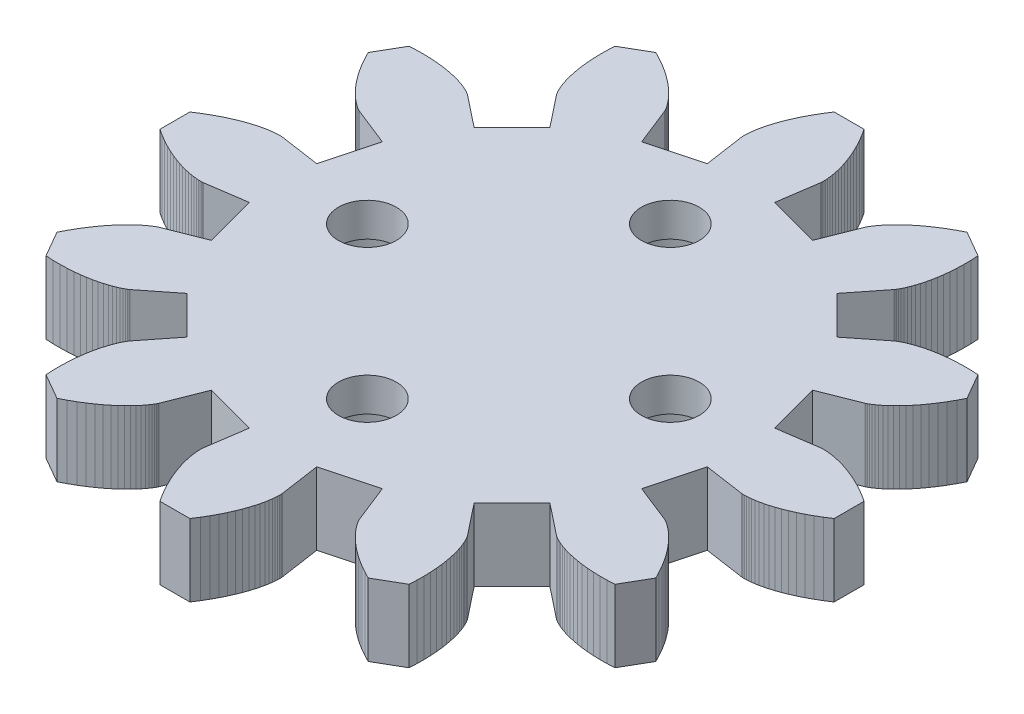
SolidWorks part; units mm, degrees
ref_plane "Front Plane" through (0, 0, 0) normal (0, 0, 1) x (1, 0, 0)
ref_plane "Top Plane" through (0, 0, 0) normal (0, 1, 0) x (1, 0, 0)
ref_plane "Right Plane" through (0, 0, 0) normal (1, 0, 0) x (0, 0, -1)
sketch "Sketch2" plane through (0, 0, 0) normal (0, 1, 0) x (1, 0, 0)
  line L0 (9.4981, 1.3948) -> (11.1567, 1.6383)
  line L1 (11.1567, 1.6383) -> (11.1651, 1.6393)
  line L2 (11.1651, 1.6393) -> (11.1903, 1.6415)
  line L3 (11.1903, 1.6415) -> (11.2326, 1.6435)
  line L4 (11.2326, 1.6435) -> (11.2917, 1.6441)
  line L5 (11.2917, 1.6441) -> (11.3678, 1.6418)
  line L6 (11.3678, 1.6418) -> (11.4606, 1.6355)
  line L7 (11.4606, 1.6355) -> (11.5699, 1.6239)
  line L8 (11.5699, 1.6239) -> (11.6954, 1.6055)
  line L9 (11.6954, 1.6055) -> (11.8367, 1.5793)
  line L10 (11.8367, 1.5793) -> (11.9934, 1.5438)
  line L11 (11.9934, 1.5438) -> (12.165, 1.498)
  line L12 (12.165, 1.498) -> (12.3508, 1.4405)
  line L13 (12.3508, 1.4405) -> (12.5502, 1.3703)
  line L14 (12.5502, 1.3703) -> (12.7624, 1.2862)
  line L15 (12.7624, 1.2862) -> (12.9867, 1.1871)
  line L16 (12.9867, 1.1871) -> (13.2222, 1.072)
  line L17 (13.2222, 1.072) -> (13.468, 0.9399)
  line L18 (13.468, 0.9399) -> (13.723, 0.7897)
  line L19 (13.723, 0.7897) -> (13.9862, 0.6207)
  line L20 (13.9862, 0.6207) -> (13.9862, -0.6207)
  line L21 (13.9862, -0.6207) -> (13.723, -0.7897)
  line L22 (13.723, -0.7897) -> (13.468, -0.9399)
  line L23 (13.468, -0.9399) -> (13.2222, -1.072)
  line L24 (13.2222, -1.072) -> (12.9867, -1.1871)
  line L25 (12.9867, -1.1871) -> (12.7624, -1.2862)
  line L26 (12.7624, -1.2862) -> (12.5502, -1.3703)
  line L27 (12.5502, -1.3703) -> (12.3508, -1.4405)
  line L28 (12.3508, -1.4405) -> (12.165, -1.498)
  line L29 (12.165, -1.498) -> (11.9934, -1.5438)
  line L30 (11.9934, -1.5438) -> (11.8367, -1.5793)
  line L31 (11.8367, -1.5793) -> (11.6954, -1.6055)
  line L32 (11.6954, -1.6055) -> (11.5699, -1.6239)
  line L33 (11.5699, -1.6239) -> (11.4606, -1.6355)
  line L34 (11.4606, -1.6355) -> (11.3678, -1.6418)
  line L35 (11.3678, -1.6418) -> (11.2917, -1.6441)
  line L36 (11.2917, -1.6441) -> (11.2326, -1.6435)
  line L37 (11.2326, -1.6435) -> (11.1903, -1.6415)
  line L38 (11.1903, -1.6415) -> (11.1651, -1.6393)
  line L39 (11.1651, -1.6393) -> (11.1567, -1.6383)
  line L40 (11.1567, -1.6383) -> (9.4981, -1.3948)
  line L41 (9.4981, -1.3948) -> (8.923, -3.5412)
  line L42 (8.923, -3.5412) -> (10.4811, -4.1595)
  line L43 (10.4811, -4.1595) -> (10.4889, -4.1628)
  line L44 (10.4889, -4.1628) -> (10.5119, -4.1736)
  line L45 (10.5119, -4.1736) -> (10.5494, -4.193)
  line L46 (10.5494, -4.193) -> (10.601, -4.2221)
  line L47 (10.601, -4.2221) -> (10.6657, -4.262)
  line L48 (10.6657, -4.262) -> (10.743, -4.3139)
  line L49 (10.743, -4.3139) -> (10.8318, -4.3786)
  line L50 (10.8318, -4.3786) -> (10.9313, -4.4573)
  line L51 (10.9313, -4.4573) -> (11.0405, -4.5507)
  line L52 (11.0405, -4.5507) -> (11.1585, -4.6597)
  line L53 (11.1585, -4.6597) -> (11.2842, -4.7852)
  line L54 (11.2842, -4.7852) -> (11.4164, -4.9279)
  line L55 (11.4164, -4.9279) -> (11.5539, -5.0883)
  line L56 (11.5539, -5.0883) -> (11.6957, -5.2673)
  line L57 (11.6957, -5.2673) -> (11.8404, -5.4653)
  line L58 (11.8404, -5.4653) -> (11.9868, -5.6827)
  line L59 (11.9868, -5.6827) -> (12.1335, -5.92)
  line L60 (12.1335, -5.92) -> (12.2793, -6.1776)
  line L61 (12.2793, -6.1776) -> (12.4228, -6.4556)
  line L62 (12.4228, -6.4556) -> (11.8021, -7.5307)
  line L63 (11.8021, -7.5307) -> (11.4896, -7.5454)
  line L64 (11.4896, -7.5454) -> (11.1937, -7.5479)
  line L65 (11.1937, -7.5479) -> (10.9148, -7.5395)
  line L66 (10.9148, -7.5395) -> (10.6533, -7.5215)
  line L67 (10.6533, -7.5215) -> (10.4095, -7.4951)
  line L68 (10.4095, -7.4951) -> (10.1836, -7.4618)
  line L69 (10.1836, -7.4618) -> (9.9758, -7.4229)
  line L70 (9.9758, -7.4229) -> (9.7862, -7.3798)
  line L71 (9.7862, -7.3798) -> (9.6147, -7.3337)
  line L72 (9.6147, -7.3337) -> (9.4613, -7.2861)
  line L73 (9.4613, -7.2861) -> (9.3258, -7.2381)
  line L74 (9.3258, -7.2381) -> (9.2079, -7.1913)
  line L75 (9.2079, -7.1913) -> (9.1074, -7.1467)
  line L76 (9.1074, -7.1467) -> (9.0239, -7.1058)
  line L77 (9.0239, -7.1058) -> (8.9569, -7.0697)
  line L78 (8.9569, -7.0697) -> (8.9059, -7.0396)
  line L79 (8.9059, -7.0396) -> (8.8704, -7.0167)
  line L80 (8.8704, -7.0167) -> (8.8496, -7.0022)
  line L81 (8.8496, -7.0022) -> (8.8428, -6.9972)
  line L82 (8.8428, -6.9972) -> (7.5282, -5.957)
  line L83 (7.5282, -5.957) -> (5.957, -7.5282)
  line L84 (5.957, -7.5282) -> (6.9972, -8.8428)
  line L85 (6.9972, -8.8428) -> (7.0022, -8.8496)
  line L86 (7.0022, -8.8496) -> (7.0167, -8.8704)
  line L87 (7.0167, -8.8704) -> (7.0396, -8.9059)
  line L88 (7.0396, -8.9059) -> (7.0697, -8.9569)
  line L89 (7.0697, -8.9569) -> (7.1058, -9.0239)
  line L90 (7.1058, -9.0239) -> (7.1467, -9.1074)
  line L91 (7.1467, -9.1074) -> (7.1913, -9.2079)
  line L92 (7.1913, -9.2079) -> (7.2381, -9.3258)
  line L93 (7.2381, -9.3258) -> (7.2861, -9.4613)
  line L94 (7.2861, -9.4613) -> (7.3337, -9.6147)
  line L95 (7.3337, -9.6147) -> (7.3798, -9.7862)
  line L96 (7.3798, -9.7862) -> (7.4229, -9.9758)
  line L97 (7.4229, -9.9758) -> (7.4618, -10.1836)
  line L98 (7.4618, -10.1836) -> (7.4951, -10.4095)
  line L99 (7.4951, -10.4095) -> (7.5215, -10.6533)
  line L100 (7.5215, -10.6533) -> (7.5395, -10.9148)
  line L101 (7.5395, -10.9148) -> (7.5479, -11.1937)
  line L102 (7.5479, -11.1937) -> (7.5454, -11.4896)
  line L103 (7.5454, -11.4896) -> (7.5307, -11.8021)
  line L104 (7.5307, -11.8021) -> (6.4556, -12.4228)
  line L105 (6.4556, -12.4228) -> (6.1776, -12.2793)
  line L106 (6.1776, -12.2793) -> (5.92, -12.1335)
  line L107 (5.92, -12.1335) -> (5.6827, -11.9868)
  line L108 (5.6827, -11.9868) -> (5.4653, -11.8404)
  line L109 (5.4653, -11.8404) -> (5.2673, -11.6957)
  line L110 (5.2673, -11.6957) -> (5.0883, -11.5539)
  line L111 (5.0883, -11.5539) -> (4.9279, -11.4164)
  line L112 (4.9279, -11.4164) -> (4.7852, -11.2842)
  line L113 (4.7852, -11.2842) -> (4.6597, -11.1585)
  line L114 (4.6597, -11.1585) -> (4.5507, -11.0405)
  line L115 (4.5507, -11.0405) -> (4.4573, -10.9313)
  line L116 (4.4573, -10.9313) -> (4.3786, -10.8318)
  line L117 (4.3786, -10.8318) -> (4.3139, -10.743)
  line L118 (4.3139, -10.743) -> (4.262, -10.6657)
  line L119 (4.262, -10.6657) -> (4.2221, -10.601)
  line L120 (4.2221, -10.601) -> (4.193, -10.5494)
  line L121 (4.193, -10.5494) -> (4.1736, -10.5119)
  line L122 (4.1736, -10.5119) -> (4.1628, -10.4889)
  line L123 (4.1628, -10.4889) -> (4.1595, -10.4811)
  line L124 (4.1595, -10.4811) -> (3.5412, -8.923)
  line L125 (3.5412, -8.923) -> (1.3948, -9.4981)
  line L126 (1.3948, -9.4981) -> (1.6383, -11.1567)
  line L127 (1.6383, -11.1567) -> (1.6393, -11.1651)
  line L128 (1.6393, -11.1651) -> (1.6415, -11.1903)
  line L129 (1.6415, -11.1903) -> (1.6435, -11.2326)
  line L130 (1.6435, -11.2326) -> (1.6441, -11.2917)
  line L131 (1.6441, -11.2917) -> (1.6418, -11.3678)
  line L132 (1.6418, -11.3678) -> (1.6355, -11.4606)
  line L133 (1.6355, -11.4606) -> (1.6239, -11.5699)
  line L134 (1.6239, -11.5699) -> (1.6055, -11.6954)
  line L135 (1.6055, -11.6954) -> (1.5793, -11.8367)
  line L136 (1.5793, -11.8367) -> (1.5438, -11.9934)
  line L137 (1.5438, -11.9934) -> (1.498, -12.165)
  line L138 (1.498, -12.165) -> (1.4405, -12.3508)
  line L139 (1.4405, -12.3508) -> (1.3703, -12.5502)
  line L140 (1.3703, -12.5502) -> (1.2862, -12.7624)
  line L141 (1.2862, -12.7624) -> (1.1871, -12.9867)
  line L142 (1.1871, -12.9867) -> (1.072, -13.2222)
  line L143 (1.072, -13.2222) -> (0.9399, -13.468)
  line L144 (0.9399, -13.468) -> (0.7897, -13.723)
  line L145 (0.7897, -13.723) -> (0.6207, -13.9862)
  line L146 (0.6207, -13.9862) -> (-0.6207, -13.9862)
  line L147 (-0.6207, -13.9862) -> (-0.7897, -13.723)
  line L148 (-0.7897, -13.723) -> (-0.9399, -13.468)
  line L149 (-0.9399, -13.468) -> (-1.072, -13.2222)
  line L150 (-1.072, -13.2222) -> (-1.1871, -12.9867)
  line L151 (-1.1871, -12.9867) -> (-1.2862, -12.7624)
  line L152 (-1.2862, -12.7624) -> (-1.3703, -12.5502)
  line L153 (-1.3703, -12.5502) -> (-1.4405, -12.3508)
  line L154 (-1.4405, -12.3508) -> (-1.498, -12.165)
  line L155 (-1.498, -12.165) -> (-1.5438, -11.9934)
  line L156 (-1.5438, -11.9934) -> (-1.5793, -11.8367)
  line L157 (-1.5793, -11.8367) -> (-1.6055, -11.6954)
  line L158 (-1.6055, -11.6954) -> (-1.6239, -11.5699)
  line L159 (-1.6239, -11.5699) -> (-1.6355, -11.4606)
  line L160 (-1.6355, -11.4606) -> (-1.6418, -11.3678)
  line L161 (-1.6418, -11.3678) -> (-1.6441, -11.2917)
  line L162 (-1.6441, -11.2917) -> (-1.6435, -11.2326)
  line L163 (-1.6435, -11.2326) -> (-1.6415, -11.1903)
  line L164 (-1.6415, -11.1903) -> (-1.6393, -11.1651)
  line L165 (-1.6393, -11.1651) -> (-1.6383, -11.1567)
  line L166 (-1.6383, -11.1567) -> (-1.3948, -9.4981)
  line L167 (-1.3948, -9.4981) -> (-3.5412, -8.923)
  line L168 (-3.5412, -8.923) -> (-4.1595, -10.4811)
  line L169 (-4.1595, -10.4811) -> (-4.1628, -10.4889)
  line L170 (-4.1628, -10.4889) -> (-4.1736, -10.5119)
  line L171 (-4.1736, -10.5119) -> (-4.193, -10.5494)
  line L172 (-4.193, -10.5494) -> (-4.2221, -10.601)
  line L173 (-4.2221, -10.601) -> (-4.262, -10.6657)
  line L174 (-4.262, -10.6657) -> (-4.3139, -10.743)
  line L175 (-4.3139, -10.743) -> (-4.3786, -10.8318)
  line L176 (-4.3786, -10.8318) -> (-4.4573, -10.9313)
  line L177 (-4.4573, -10.9313) -> (-4.5507, -11.0405)
  line L178 (-4.5507, -11.0405) -> (-4.6597, -11.1585)
  line L179 (-4.6597, -11.1585) -> (-4.7852, -11.2842)
  line L180 (-4.7852, -11.2842) -> (-4.9279, -11.4164)
  line L181 (-4.9279, -11.4164) -> (-5.0883, -11.5539)
  line L182 (-5.0883, -11.5539) -> (-5.2673, -11.6957)
  line L183 (-5.2673, -11.6957) -> (-5.4653, -11.8404)
  line L184 (-5.4653, -11.8404) -> (-5.6827, -11.9868)
  line L185 (-5.6827, -11.9868) -> (-5.92, -12.1335)
  line L186 (-5.92, -12.1335) -> (-6.1776, -12.2793)
  line L187 (-6.1776, -12.2793) -> (-6.4556, -12.4228)
  line L188 (-6.4556, -12.4228) -> (-7.5307, -11.8021)
  line L189 (-7.5307, -11.8021) -> (-7.5454, -11.4896)
  line L190 (-7.5454, -11.4896) -> (-7.5479, -11.1937)
  line L191 (-7.5479, -11.1937) -> (-7.5395, -10.9148)
  line L192 (-7.5395, -10.9148) -> (-7.5215, -10.6533)
  line L193 (-7.5215, -10.6533) -> (-7.4951, -10.4095)
  line L194 (-7.4951, -10.4095) -> (-7.4618, -10.1836)
  line L195 (-7.4618, -10.1836) -> (-7.4229, -9.9758)
  line L196 (-7.4229, -9.9758) -> (-7.3798, -9.7862)
  line L197 (-7.3798, -9.7862) -> (-7.3337, -9.6147)
  line L198 (-7.3337, -9.6147) -> (-7.2861, -9.4613)
  line L199 (-7.2861, -9.4613) -> (-7.2381, -9.3258)
  line L200 (-7.2381, -9.3258) -> (-7.1913, -9.2079)
  line L201 (-7.1913, -9.2079) -> (-7.1467, -9.1074)
  line L202 (-7.1467, -9.1074) -> (-7.1058, -9.0239)
  line L203 (-7.1058, -9.0239) -> (-7.0697, -8.9569)
  line L204 (-7.0697, -8.9569) -> (-7.0396, -8.9059)
  line L205 (-7.0396, -8.9059) -> (-7.0167, -8.8704)
  line L206 (-7.0167, -8.8704) -> (-7.0022, -8.8496)
  line L207 (-7.0022, -8.8496) -> (-6.9972, -8.8428)
  line L208 (-6.9972, -8.8428) -> (-5.957, -7.5282)
  line L209 (-5.957, -7.5282) -> (-7.5282, -5.957)
  line L210 (-7.5282, -5.957) -> (-8.8428, -6.9972)
  line L211 (-8.8428, -6.9972) -> (-8.8496, -7.0022)
  line L212 (-8.8496, -7.0022) -> (-8.8704, -7.0167)
  line L213 (-8.8704, -7.0167) -> (-8.9059, -7.0396)
  line L214 (-8.9059, -7.0396) -> (-8.9569, -7.0697)
  line L215 (-8.9569, -7.0697) -> (-9.0239, -7.1058)
  line L216 (-9.0239, -7.1058) -> (-9.1074, -7.1467)
  line L217 (-9.1074, -7.1467) -> (-9.2079, -7.1913)
  line L218 (-9.2079, -7.1913) -> (-9.3258, -7.2381)
  line L219 (-9.3258, -7.2381) -> (-9.4613, -7.2861)
  line L220 (-9.4613, -7.2861) -> (-9.6147, -7.3337)
  line L221 (-9.6147, -7.3337) -> (-9.7862, -7.3798)
  line L222 (-9.7862, -7.3798) -> (-9.9758, -7.4229)
  line L223 (-9.9758, -7.4229) -> (-10.1836, -7.4618)
  line L224 (-10.1836, -7.4618) -> (-10.4095, -7.4951)
  line L225 (-10.4095, -7.4951) -> (-10.6533, -7.5215)
  line L226 (-10.6533, -7.5215) -> (-10.9148, -7.5395)
  line L227 (-10.9148, -7.5395) -> (-11.1937, -7.5479)
  line L228 (-11.1937, -7.5479) -> (-11.4896, -7.5454)
  line L229 (-11.4896, -7.5454) -> (-11.8021, -7.5307)
  line L230 (-11.8021, -7.5307) -> (-12.4228, -6.4556)
  line L231 (-12.4228, -6.4556) -> (-12.2793, -6.1776)
  line L232 (-12.2793, -6.1776) -> (-12.1335, -5.92)
  line L233 (-12.1335, -5.92) -> (-11.9868, -5.6827)
  line L234 (-11.9868, -5.6827) -> (-11.8404, -5.4653)
  line L235 (-11.8404, -5.4653) -> (-11.6957, -5.2673)
  line L236 (-11.6957, -5.2673) -> (-11.5539, -5.0883)
  line L237 (-11.5539, -5.0883) -> (-11.4164, -4.9279)
  line L238 (-11.4164, -4.9279) -> (-11.2842, -4.7852)
  line L239 (-11.2842, -4.7852) -> (-11.1585, -4.6597)
  line L240 (-11.1585, -4.6597) -> (-11.0405, -4.5507)
  line L241 (-11.0405, -4.5507) -> (-10.9313, -4.4573)
  line L242 (-10.9313, -4.4573) -> (-10.8318, -4.3786)
  line L243 (-10.8318, -4.3786) -> (-10.743, -4.3139)
  line L244 (-10.743, -4.3139) -> (-10.6657, -4.262)
  line L245 (-10.6657, -4.262) -> (-10.601, -4.2221)
  line L246 (-10.601, -4.2221) -> (-10.5494, -4.193)
  line L247 (-10.5494, -4.193) -> (-10.5119, -4.1736)
  line L248 (-10.5119, -4.1736) -> (-10.4889, -4.1628)
  line L249 (-10.4889, -4.1628) -> (-10.4811, -4.1595)
  line L250 (-10.4811, -4.1595) -> (-8.923, -3.5412)
  line L251 (-8.923, -3.5412) -> (-9.4981, -1.3948)
  line L252 (-9.4981, -1.3948) -> (-11.1567, -1.6383)
  line L253 (-11.1567, -1.6383) -> (-11.1651, -1.6393)
  line L254 (-11.1651, -1.6393) -> (-11.1903, -1.6415)
  line L255 (-11.1903, -1.6415) -> (-11.2326, -1.6435)
  line L256 (-11.2326, -1.6435) -> (-11.2917, -1.6441)
  line L257 (-11.2917, -1.6441) -> (-11.3678, -1.6418)
  line L258 (-11.3678, -1.6418) -> (-11.4606, -1.6355)
  line L259 (-11.4606, -1.6355) -> (-11.5699, -1.6239)
  line L260 (-11.5699, -1.6239) -> (-11.6954, -1.6055)
  line L261 (-11.6954, -1.6055) -> (-11.8367, -1.5793)
  line L262 (-11.8367, -1.5793) -> (-11.9934, -1.5438)
  line L263 (-11.9934, -1.5438) -> (-12.165, -1.498)
  line L264 (-12.165, -1.498) -> (-12.3508, -1.4405)
  line L265 (-12.3508, -1.4405) -> (-12.5502, -1.3703)
  line L266 (-12.5502, -1.3703) -> (-12.7624, -1.2862)
  line L267 (-12.7624, -1.2862) -> (-12.9867, -1.1871)
  line L268 (-12.9867, -1.1871) -> (-13.2222, -1.072)
  line L269 (-13.2222, -1.072) -> (-13.468, -0.9399)
  line L270 (-13.468, -0.9399) -> (-13.723, -0.7897)
  line L271 (-13.723, -0.7897) -> (-13.9862, -0.6207)
  line L272 (-13.9862, -0.6207) -> (-13.9862, 0.6207)
  line L273 (-13.9862, 0.6207) -> (-13.723, 0.7897)
  line L274 (-13.723, 0.7897) -> (-13.468, 0.9399)
  line L275 (-13.468, 0.9399) -> (-13.2222, 1.072)
  line L276 (-13.2222, 1.072) -> (-12.9867, 1.1871)
  line L277 (-12.9867, 1.1871) -> (-12.7624, 1.2862)
  line L278 (-12.7624, 1.2862) -> (-12.5502, 1.3703)
  line L279 (-12.5502, 1.3703) -> (-12.3508, 1.4405)
  line L280 (-12.3508, 1.4405) -> (-12.165, 1.498)
  line L281 (-12.165, 1.498) -> (-11.9934, 1.5438)
  line L282 (-11.9934, 1.5438) -> (-11.8367, 1.5793)
  line L283 (-11.8367, 1.5793) -> (-11.6954, 1.6055)
  line L284 (-11.6954, 1.6055) -> (-11.5699, 1.6239)
  line L285 (-11.5699, 1.6239) -> (-11.4606, 1.6355)
  line L286 (-11.4606, 1.6355) -> (-11.3678, 1.6418)
  line L287 (-11.3678, 1.6418) -> (-11.2917, 1.6441)
  line L288 (-11.2917, 1.6441) -> (-11.2326, 1.6435)
  line L289 (-11.2326, 1.6435) -> (-11.1903, 1.6415)
  line L290 (-11.1903, 1.6415) -> (-11.1651, 1.6393)
  line L291 (-11.1651, 1.6393) -> (-11.1567, 1.6383)
  line L292 (-11.1567, 1.6383) -> (-9.4981, 1.3948)
  line L293 (-9.4981, 1.3948) -> (-8.923, 3.5412)
  line L294 (-8.923, 3.5412) -> (-10.4811, 4.1595)
  line L295 (-10.4811, 4.1595) -> (-10.4889, 4.1628)
  line L296 (-10.4889, 4.1628) -> (-10.5119, 4.1736)
  line L297 (-10.5119, 4.1736) -> (-10.5494, 4.193)
  line L298 (-10.5494, 4.193) -> (-10.601, 4.2221)
  line L299 (-10.601, 4.2221) -> (-10.6657, 4.262)
  line L300 (-10.6657, 4.262) -> (-10.743, 4.3139)
  line L301 (-10.743, 4.3139) -> (-10.8318, 4.3786)
  line L302 (-10.8318, 4.3786) -> (-10.9313, 4.4573)
  line L303 (-10.9313, 4.4573) -> (-11.0405, 4.5507)
  line L304 (-11.0405, 4.5507) -> (-11.1585, 4.6597)
  line L305 (-11.1585, 4.6597) -> (-11.2842, 4.7852)
  line L306 (-11.2842, 4.7852) -> (-11.4164, 4.9279)
  line L307 (-11.4164, 4.9279) -> (-11.5539, 5.0883)
  line L308 (-11.5539, 5.0883) -> (-11.6957, 5.2673)
  line L309 (-11.6957, 5.2673) -> (-11.8404, 5.4653)
  line L310 (-11.8404, 5.4653) -> (-11.9868, 5.6827)
  line L311 (-11.9868, 5.6827) -> (-12.1335, 5.92)
  line L312 (-12.1335, 5.92) -> (-12.2793, 6.1776)
  line L313 (-12.2793, 6.1776) -> (-12.4228, 6.4556)
  line L314 (-12.4228, 6.4556) -> (-11.8021, 7.5307)
  line L315 (-11.8021, 7.5307) -> (-11.4896, 7.5454)
  line L316 (-11.4896, 7.5454) -> (-11.1937, 7.5479)
  line L317 (-11.1937, 7.5479) -> (-10.9148, 7.5395)
  line L318 (-10.9148, 7.5395) -> (-10.6533, 7.5215)
  line L319 (-10.6533, 7.5215) -> (-10.4095, 7.4951)
  line L320 (-10.4095, 7.4951) -> (-10.1836, 7.4618)
  line L321 (-10.1836, 7.4618) -> (-9.9758, 7.4229)
  line L322 (-9.9758, 7.4229) -> (-9.7862, 7.3798)
  line L323 (-9.7862, 7.3798) -> (-9.6147, 7.3337)
  line L324 (-9.6147, 7.3337) -> (-9.4613, 7.2861)
  line L325 (-9.4613, 7.2861) -> (-9.3258, 7.2381)
  line L326 (-9.3258, 7.2381) -> (-9.2079, 7.1913)
  line L327 (-9.2079, 7.1913) -> (-9.1074, 7.1467)
  line L328 (-9.1074, 7.1467) -> (-9.0239, 7.1058)
  line L329 (-9.0239, 7.1058) -> (-8.9569, 7.0697)
  line L330 (-8.9569, 7.0697) -> (-8.9059, 7.0396)
  line L331 (-8.9059, 7.0396) -> (-8.8704, 7.0167)
  line L332 (-8.8704, 7.0167) -> (-8.8496, 7.0022)
  line L333 (-8.8496, 7.0022) -> (-8.8428, 6.9972)
  line L334 (-8.8428, 6.9972) -> (-7.5282, 5.957)
  line L335 (-7.5282, 5.957) -> (-5.957, 7.5282)
  line L336 (-5.957, 7.5282) -> (-6.9972, 8.8428)
  line L337 (-6.9972, 8.8428) -> (-7.0022, 8.8496)
  line L338 (-7.0022, 8.8496) -> (-7.0167, 8.8704)
  line L339 (-7.0167, 8.8704) -> (-7.0396, 8.9059)
  line L340 (-7.0396, 8.9059) -> (-7.0697, 8.9569)
  line L341 (-7.0697, 8.9569) -> (-7.1058, 9.0239)
  line L342 (-7.1058, 9.0239) -> (-7.1467, 9.1074)
  line L343 (-7.1467, 9.1074) -> (-7.1913, 9.2079)
  line L344 (-7.1913, 9.2079) -> (-7.2381, 9.3258)
  line L345 (-7.2381, 9.3258) -> (-7.2861, 9.4613)
  line L346 (-7.2861, 9.4613) -> (-7.3337, 9.6147)
  line L347 (-7.3337, 9.6147) -> (-7.3798, 9.7862)
  line L348 (-7.3798, 9.7862) -> (-7.4229, 9.9758)
  line L349 (-7.4229, 9.9758) -> (-7.4618, 10.1836)
  line L350 (-7.4618, 10.1836) -> (-7.4951, 10.4095)
  line L351 (-7.4951, 10.4095) -> (-7.5215, 10.6533)
  line L352 (-7.5215, 10.6533) -> (-7.5395, 10.9148)
  line L353 (-7.5395, 10.9148) -> (-7.5479, 11.1937)
  line L354 (-7.5479, 11.1937) -> (-7.5454, 11.4896)
  line L355 (-7.5454, 11.4896) -> (-7.5307, 11.8021)
  line L356 (-7.5307, 11.8021) -> (-6.4556, 12.4228)
  line L357 (-6.4556, 12.4228) -> (-6.1776, 12.2793)
  line L358 (-6.1776, 12.2793) -> (-5.92, 12.1335)
  line L359 (-5.92, 12.1335) -> (-5.6827, 11.9868)
  line L360 (-5.6827, 11.9868) -> (-5.4653, 11.8404)
  line L361 (-5.4653, 11.8404) -> (-5.2673, 11.6957)
  line L362 (-5.2673, 11.6957) -> (-5.0883, 11.5539)
  line L363 (-5.0883, 11.5539) -> (-4.9279, 11.4164)
  line L364 (-4.9279, 11.4164) -> (-4.7852, 11.2842)
  line L365 (-4.7852, 11.2842) -> (-4.6597, 11.1585)
  line L366 (-4.6597, 11.1585) -> (-4.5507, 11.0405)
  line L367 (-4.5507, 11.0405) -> (-4.4573, 10.9313)
  line L368 (-4.4573, 10.9313) -> (-4.3786, 10.8318)
  line L369 (-4.3786, 10.8318) -> (-4.3139, 10.743)
  line L370 (-4.3139, 10.743) -> (-4.262, 10.6657)
  line L371 (-4.262, 10.6657) -> (-4.2221, 10.601)
  line L372 (-4.2221, 10.601) -> (-4.193, 10.5494)
  line L373 (-4.193, 10.5494) -> (-4.1736, 10.5119)
  line L374 (-4.1736, 10.5119) -> (-4.1628, 10.4889)
  line L375 (-4.1628, 10.4889) -> (-4.1595, 10.4811)
  line L376 (-4.1595, 10.4811) -> (-3.5412, 8.923)
  line L377 (-3.5412, 8.923) -> (-1.3948, 9.4981)
  line L378 (-1.3948, 9.4981) -> (-1.6383, 11.1567)
  line L379 (-1.6383, 11.1567) -> (-1.6393, 11.1651)
  line L380 (-1.6393, 11.1651) -> (-1.6415, 11.1903)
  line L381 (-1.6415, 11.1903) -> (-1.6435, 11.2326)
  line L382 (-1.6435, 11.2326) -> (-1.6441, 11.2917)
  line L383 (-1.6441, 11.2917) -> (-1.6418, 11.3678)
  line L384 (-1.6418, 11.3678) -> (-1.6355, 11.4606)
  line L385 (-1.6355, 11.4606) -> (-1.6239, 11.5699)
  line L386 (-1.6239, 11.5699) -> (-1.6055, 11.6954)
  line L387 (-1.6055, 11.6954) -> (-1.5793, 11.8367)
  line L388 (-1.5793, 11.8367) -> (-1.5438, 11.9934)
  line L389 (-1.5438, 11.9934) -> (-1.498, 12.165)
  line L390 (-1.498, 12.165) -> (-1.4405, 12.3508)
  line L391 (-1.4405, 12.3508) -> (-1.3703, 12.5502)
  line L392 (-1.3703, 12.5502) -> (-1.2862, 12.7624)
  line L393 (-1.2862, 12.7624) -> (-1.1871, 12.9867)
  line L394 (-1.1871, 12.9867) -> (-1.072, 13.2222)
  line L395 (-1.072, 13.2222) -> (-0.9399, 13.468)
  line L396 (-0.9399, 13.468) -> (-0.7897, 13.723)
  line L397 (-0.7897, 13.723) -> (-0.6207, 13.9862)
  line L398 (-0.6207, 13.9862) -> (0.6207, 13.9862)
  line L399 (0.6207, 13.9862) -> (0.7897, 13.723)
  line L400 (0.7897, 13.723) -> (0.9399, 13.468)
  line L401 (0.9399, 13.468) -> (1.072, 13.2222)
  line L402 (1.072, 13.2222) -> (1.1871, 12.9867)
  line L403 (1.1871, 12.9867) -> (1.2862, 12.7624)
  line L404 (1.2862, 12.7624) -> (1.3703, 12.5502)
  line L405 (1.3703, 12.5502) -> (1.4405, 12.3508)
  line L406 (1.4405, 12.3508) -> (1.498, 12.165)
  line L407 (1.498, 12.165) -> (1.5438, 11.9934)
  line L408 (1.5438, 11.9934) -> (1.5793, 11.8367)
  line L409 (1.5793, 11.8367) -> (1.6055, 11.6954)
  line L410 (1.6055, 11.6954) -> (1.6239, 11.5699)
  line L411 (1.6239, 11.5699) -> (1.6355, 11.4606)
  line L412 (1.6355, 11.4606) -> (1.6418, 11.3678)
  line L413 (1.6418, 11.3678) -> (1.6441, 11.2917)
  line L414 (1.6441, 11.2917) -> (1.6435, 11.2326)
  line L415 (1.6435, 11.2326) -> (1.6415, 11.1903)
  line L416 (1.6415, 11.1903) -> (1.6393, 11.1651)
  line L417 (1.6393, 11.1651) -> (1.6383, 11.1567)
  line L418 (1.6383, 11.1567) -> (1.3948, 9.4981)
  line L419 (1.3948, 9.4981) -> (3.5412, 8.923)
  line L420 (3.5412, 8.923) -> (4.1595, 10.4811)
  line L421 (4.1595, 10.4811) -> (4.1628, 10.4889)
  line L422 (4.1628, 10.4889) -> (4.1736, 10.5119)
  line L423 (4.1736, 10.5119) -> (4.193, 10.5494)
  line L424 (4.193, 10.5494) -> (4.2221, 10.601)
  line L425 (4.2221, 10.601) -> (4.262, 10.6657)
  line L426 (4.262, 10.6657) -> (4.3139, 10.743)
  line L427 (4.3139, 10.743) -> (4.3786, 10.8318)
  line L428 (4.3786, 10.8318) -> (4.4573, 10.9313)
  line L429 (4.4573, 10.9313) -> (4.5507, 11.0405)
  line L430 (4.5507, 11.0405) -> (4.6597, 11.1585)
  line L431 (4.6597, 11.1585) -> (4.7852, 11.2842)
  line L432 (4.7852, 11.2842) -> (4.9279, 11.4164)
  line L433 (4.9279, 11.4164) -> (5.0883, 11.5539)
  line L434 (5.0883, 11.5539) -> (5.2673, 11.6957)
  line L435 (5.2673, 11.6957) -> (5.4653, 11.8404)
  line L436 (5.4653, 11.8404) -> (5.6827, 11.9868)
  line L437 (5.6827, 11.9868) -> (5.92, 12.1335)
  line L438 (5.92, 12.1335) -> (6.1776, 12.2793)
  line L439 (6.1776, 12.2793) -> (6.4556, 12.4228)
  line L440 (6.4556, 12.4228) -> (7.5307, 11.8021)
  line L441 (7.5307, 11.8021) -> (7.5454, 11.4896)
  line L442 (7.5454, 11.4896) -> (7.5479, 11.1937)
  line L443 (7.5479, 11.1937) -> (7.5395, 10.9148)
  line L444 (7.5395, 10.9148) -> (7.5215, 10.6533)
  line L445 (7.5215, 10.6533) -> (7.4951, 10.4095)
  line L446 (7.4951, 10.4095) -> (7.4618, 10.1836)
  line L447 (7.4618, 10.1836) -> (7.4229, 9.9758)
  line L448 (7.4229, 9.9758) -> (7.3798, 9.7862)
  line L449 (7.3798, 9.7862) -> (7.3337, 9.6147)
  line L450 (7.3337, 9.6147) -> (7.2861, 9.4613)
  line L451 (7.2861, 9.4613) -> (7.2381, 9.3258)
  line L452 (7.2381, 9.3258) -> (7.1913, 9.2079)
  line L453 (7.1913, 9.2079) -> (7.1467, 9.1074)
  line L454 (7.1467, 9.1074) -> (7.1058, 9.0239)
  line L455 (7.1058, 9.0239) -> (7.0697, 8.9569)
  line L456 (7.0697, 8.9569) -> (7.0396, 8.9059)
  line L457 (7.0396, 8.9059) -> (7.0167, 8.8704)
  line L458 (7.0167, 8.8704) -> (7.0022, 8.8496)
  line L459 (7.0022, 8.8496) -> (6.9972, 8.8428)
  line L460 (6.9972, 8.8428) -> (5.957, 7.5282)
  line L461 (5.957, 7.5282) -> (7.5282, 5.957)
  line L462 (7.5282, 5.957) -> (8.8428, 6.9972)
  line L463 (8.8428, 6.9972) -> (8.8496, 7.0022)
  line L464 (8.8496, 7.0022) -> (8.8704, 7.0167)
  line L465 (8.8704, 7.0167) -> (8.9059, 7.0396)
  line L466 (8.9059, 7.0396) -> (8.9569, 7.0697)
  line L467 (8.9569, 7.0697) -> (9.0239, 7.1058)
  line L468 (9.0239, 7.1058) -> (9.1074, 7.1467)
  line L469 (9.1074, 7.1467) -> (9.2079, 7.1913)
  line L470 (9.2079, 7.1913) -> (9.3258, 7.2381)
  line L471 (9.3258, 7.2381) -> (9.4613, 7.2861)
  line L472 (9.4613, 7.2861) -> (9.6147, 7.3337)
  line L473 (9.6147, 7.3337) -> (9.7862, 7.3798)
  line L474 (9.7862, 7.3798) -> (9.9758, 7.4229)
  line L475 (9.9758, 7.4229) -> (10.1836, 7.4618)
  line L476 (10.1836, 7.4618) -> (10.4095, 7.4951)
  line L477 (10.4095, 7.4951) -> (10.6533, 7.5215)
  line L478 (10.6533, 7.5215) -> (10.9148, 7.5395)
  line L479 (10.9148, 7.5395) -> (11.1937, 7.5479)
  line L480 (11.1937, 7.5479) -> (11.4896, 7.5454)
  line L481 (11.4896, 7.5454) -> (11.8021, 7.5307)
  line L482 (11.8021, 7.5307) -> (12.4228, 6.4556)
  line L483 (12.4228, 6.4556) -> (12.2793, 6.1776)
  line L484 (12.2793, 6.1776) -> (12.1335, 5.92)
  line L485 (12.1335, 5.92) -> (11.9868, 5.6827)
  line L486 (11.9868, 5.6827) -> (11.8404, 5.4653)
  line L487 (11.8404, 5.4653) -> (11.6957, 5.2673)
  line L488 (11.6957, 5.2673) -> (11.5539, 5.0883)
  line L489 (11.5539, 5.0883) -> (11.4164, 4.9279)
  line L490 (11.4164, 4.9279) -> (11.2842, 4.7852)
  line L491 (11.2842, 4.7852) -> (11.1585, 4.6597)
  line L492 (11.1585, 4.6597) -> (11.0405, 4.5507)
  line L493 (11.0405, 4.5507) -> (10.9313, 4.4573)
  line L494 (10.9313, 4.4573) -> (10.8318, 4.3786)
  line L495 (10.8318, 4.3786) -> (10.743, 4.3139)
  line L496 (10.743, 4.3139) -> (10.6657, 4.262)
  line L497 (10.6657, 4.262) -> (10.601, 4.2221)
  line L498 (10.601, 4.2221) -> (10.5494, 4.193)
  line L499 (10.5494, 4.193) -> (10.5119, 4.1736)
  line L500 (10.5119, 4.1736) -> (10.4889, 4.1628)
  line L501 (10.4889, 4.1628) -> (10.4811, 4.1595)
  line L502 (10.4811, 4.1595) -> (8.923, 3.5412)
  line L503 (8.923, 3.5412) -> (9.4981, 1.3948)
extrude "Boss-Extrude1" add sketch "Sketch2" along normal blind 3
sketch "Sketch3" plane through (0, 0, 0) normal (0, -1, 0) x (1, 0, 0)
  circle A0 centre (0, 6) radius 1
  point P0 (0, 6)
  dimension "D2" = 2
  dimension "D1" = 6
hole_wizard "CBORE for M2 Pan Head Screw1" positions "Sketch3" profile "Sketch4" counterbore size "M2" standard "DIN"
sketch "Sketch4" plane through (0, 0, 6) normal (1, 0, 0) x (0, 0, -1)
  line L0 (0, 0) -> (0, 3.721)
  line L1 (0, 3.721) -> (1.2, 3)
  line L2 (1.2, 3) -> (1.2, 1.6)
  line L3 (1.2, 1.6) -> (2.5, 1.6)
  line L4 (2.5, 1.6) -> (2.5, 0)
  line L5 (2.5, 0) -> (0, 0)
  line L10 (0, 3.721) -> (-1.2, 3) construction
  line L11 (0, -6.35) -> (0, 107.95) construction
  dimension "Hole Dia." = 2.4
  dimension "Hole Depth" = 3
  dimension "C'Bore Dia." = 5
  dimension "C'Bore Depth" = 1.6
  dimension "Drill Angle" = 118
pattern_circular "CirPattern1" count 4 over 360 about axis through (0, 0, -0.2844) along (0, 1, 0) of "CBORE for M2 Pan Head Screw1"
equation "\"z\"= 20'Number of teeth"
equation "\"m\"= 2'module in mm"
equation "\"alpha\"= 20deg'pressure angle"
equation "\"r_b\"= cos ( \"alpha\" ) * \"m\" * \"z\" / 2'base circle radius"
equation "\"r\"= \"m\" * \"z\" / 2'pitch circle radius"
equation "\"r_a\"= \"m\" * ( \"z\" + 2 ) / 2'addendum circle radius"
equation "\"r_f\"= \"m\" * ( \"z\" - 2.5 ) / 2'safe depth"
equation "\"p\"= \"m\" * 3.14'circular pitch"
